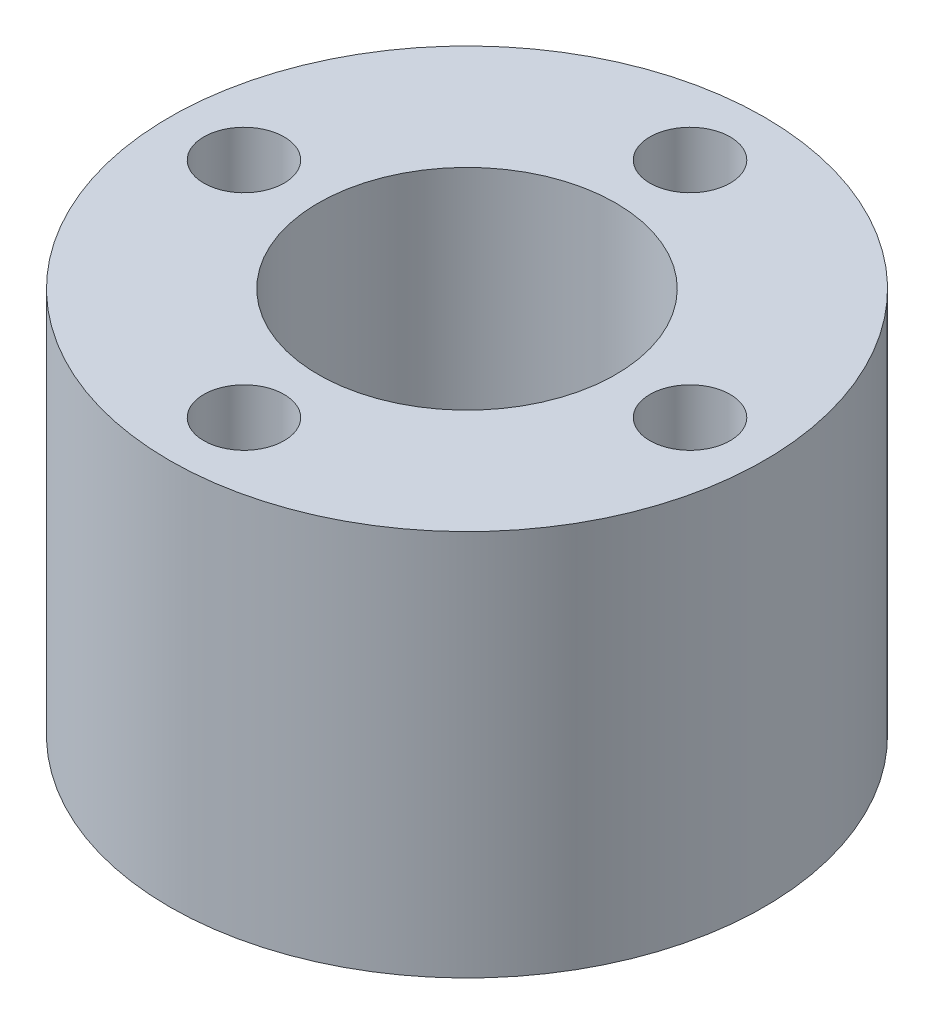
SolidWorks part; units mm, degrees
material "304不锈钢"
ref_plane "前视基准面" through (0, 0, 0) normal (0, 0, 1) x (1, 0, 0)
ref_plane "上视基准面" through (0, 0, 0) normal (0, 1, 0) x (1, 0, 0)
ref_plane "右视基准面" through (0, 0, 0) normal (1, 0, 0) x (0, 0, -1)
sketch "草图1" plane through (0, 0, 0) normal (0, 1, 0) x (1, 0, 0)
  circle A0 centre (0, 0) radius 5
  circle A1 centre (0, 0) radius 10
  dimension "D1" = 10
  dimension "D2" = 20
extrude "凸台-拉伸1" add sketch "草图1" along normal blind 13
sketch "草图2" plane through (0, 13, 0) normal (0, 1, 0) x (1, 0, 0)
  circle A0 centre (0, 7.5) radius 1.35
  dimension "D1" = 2.7
  dimension "D2" = 7.5
extrude "切除-拉伸1" cut sketch "草图2" against normal blind 6.5
hole_wizard "M2.5 螺纹孔1" positions "草图4" profile "草图5" tap size "M2.5" standard "GB"
sketch "草图4" plane through (0, 6.5, 0) normal (0, 1, 0) x (1, 0, 0)
  point P0 (0, 7.5)
sketch "草图5" plane through (0, 6.5, -7.5) normal (1, 0, 0) x (0, 0, 1)
  line L0 (0, 0) -> (0, 27.8659)
  line L1 (0, 27.8659) -> (1.025, 27.25)
  line L2 (1.025, 27.25) -> (1.025, 0)
  line L5 (1.025, 0) -> (0, 0)
  line L10 (0, 27.8659) -> (-1.025, 27.25) construction
  line L11 (0, -6.35) -> (0, 107.95) construction
  dimension "螺纹孔钻头直径" = 2.05
  dimension "螺纹孔钻头深度" = 27.25
  dimension "导头角度" = 118
cosmetic thread "孔螺蚊线1" parameters "D1"=6.5, "D2"=2.5
pattern_circular "阵列(圆周)1" count 4 over 360 about axis through (0, 0, 0) along (0, 1, 0) of "切除-拉伸1", "M2.5 螺纹孔1"
